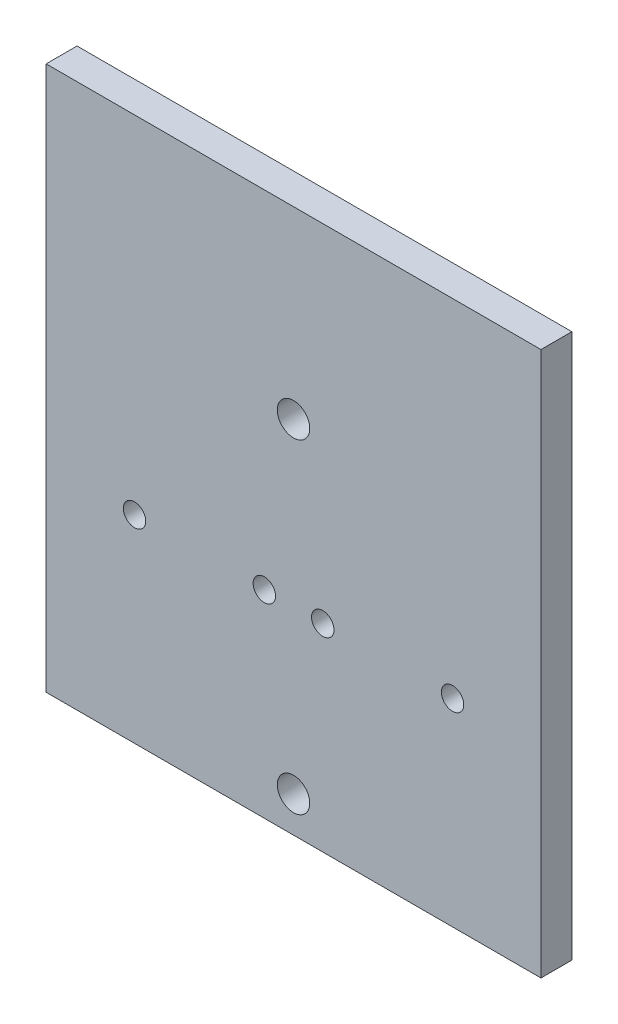
SolidWorks part; units mm, degrees
ref_plane "Front Plane" through (0, 0, 0) normal (0, 0, 1) x (1, 0, 0)
ref_plane "Top Plane" through (0, 0, 0) normal (0, 1, 0) x (1, 0, 0)
ref_plane "Right Plane" through (0, 0, 0) normal (1, 0, 0) x (0, 0, -1)
sketch "Sketch1" plane through (0, 0, 0) normal (0, 0, 1) x (1, 0, 0)
  line L0 (0, 30.5) -> (0, -30.5)
  line L1 (-5.08, 30.5) -> (5.08, 30.5)
  line L2 (-5.08, 30.5) -> (-5.08, -30.5)
  line L3 (-5.08, -30.5) -> (5.08, -30.5)
  line L4 (5.08, 30.5) -> (5.08, -30.5)
  line L5 (-30.5, 0) -> (30.5, 0)
  line L6 (-30.5, 5.08) -> (30.5, 5.08)
  line L7 (-30.5, 5.08) -> (-30.5, -5.08)
  line L8 (-30.5, -5.08) -> (30.5, -5.08)
  line L9 (30.5, 5.08) -> (30.5, -5.08)
  line L10 (5.08, -30.5) -> (30.5, -30.5)
  line L11 (30.5, -30.5) -> (30.5, -5.08)
  line L12 (30.5, 5.08) -> (30.5, 30.5)
  line L13 (30.5, 30.5) -> (-30.5, 30.5)
  line L14 (-30.5, 30.5) -> (-30.5, -30.5)
  line L15 (-30.5, -30.5) -> (-5.08, -30.5)
  circle A0 centre (0, 25) radius 2.5
  circle A1 centre (0, -25) radius 2.5
  circle A2 centre (-24.5, 0) radius 1.7272
  circle A3 centre (24.5, 0) radius 1.7272
  circle A4 centre (-4.5, 0) radius 1.7272
  circle A5 centre (4.5, 0) radius 1.7272
  dimension "D5" = 50
  dimension "D11" = 49
  dimension "D13" = 20
  dimension "D14" = 20
  dimension "D1" = 61
  dimension "D2" = 30.5
  dimension "D3" = 10.16
  dimension "D4" = 5.08
  dimension "D6" = 25
  dimension "D7" = 61
  dimension "D8" = 30.5
  dimension "D9" = 10.16
  dimension "D10" = 5.08
  dimension "D12" = 24.5
extrude "Boss-Extrude5" add sketch "Sketch1" along normal blind 4.7625 contours A0 L0 L1 L2 L6 | A0 L0 L6 L4 L1 | A5 L5 A3 L9 L6 L4 | A5 L4 L8 L9 L5 A3 | A5 L5 L0 L8 L4 | A4 L2 L8 L0 L5 | A5 L4 L6 L0 L5 | A4 L5 L0 L6 L2 | A4 L2 L6 L7 L5 A2 | A4 L5 A2 L7 L8 L2 | A1 L0 L8 L2 L3 | A1 L0 L3 L4 L8 | L13 L14 L6 L2 | L12 L13 L4 L6 | L10 L11 L8 L4 | L14 L15 L2 L8
sketch "Sketch3" plane through (-30.5, 0, 0) normal (-1, 0, 0) x (0, 0, 1)
  line L1 (0, -30.5) -> (4.7625, -30.5)
  line L2 (0, -30.5) -> (0, 30.5)
  line L3 (0, 30.5) -> (4.7625, 30.5)
  line L4 (4.7625, -30.5) -> (4.7625, 30.5)
extrude "Boss-Extrude6" add sketch "Sketch3" along normal blind 7.62
sketch "Sketch4" plane through (30.5, 0, 0) normal (1, 0, 0) x (0, 0, -1)
  line L1 (-4.7625, -30.5) -> (0, -30.5)
  line L2 (-4.7625, -30.5) -> (-4.7625, 30.5)
  line L3 (-4.7625, 30.5) -> (0, 30.5)
  line L4 (0, -30.5) -> (0, 30.5)
extrude "Boss-Extrude7" add sketch "Sketch4" along normal blind 7.62
sketch "Sketch5" plane through (0, 30.5, 0) normal (0, 1, 0) x (1, 0, 0)
  line L1 (-38.12, -4.7625) -> (38.12, -4.7625)
  line L2 (-38.12, -4.7625) -> (-38.12, 0)
  line L3 (-38.12, 0) -> (38.12, 0)
  line L4 (38.12, -4.7625) -> (38.12, 0)
extrude "Boss-Extrude8" add sketch "Sketch5" along normal blind 22.86
